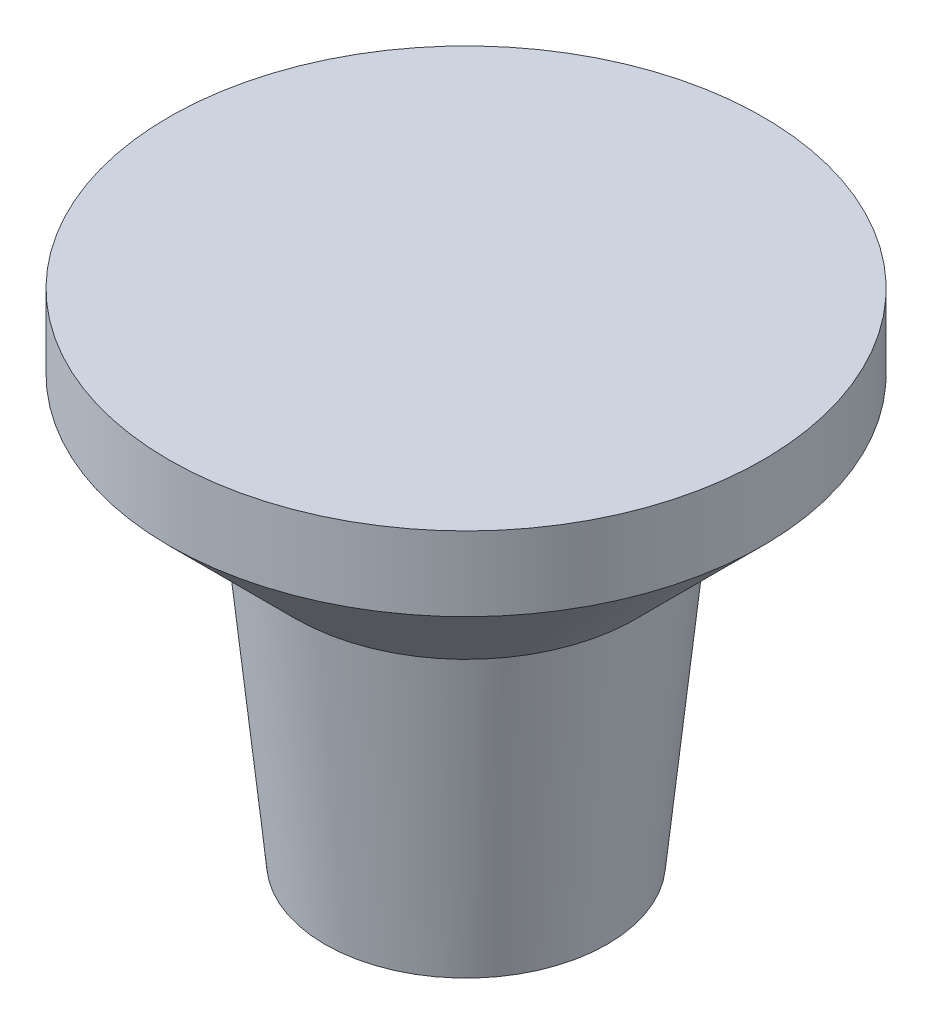
SolidWorks part; units mm, degrees
ref_plane "Płaszczyzna przednia" through (0, 0, 0) normal (0, 0, 1) x (1, 0, 0)
ref_plane "Płaszczyzna górna" through (0, 0, 0) normal (0, 1, 0) x (1, 0, 0)
ref_plane "Płaszczyzna prawa" through (0, 0, 0) normal (1, 0, 0) x (0, 0, -1)
ref_axis "Axis1" through (0, 55, 0) along (0, -1, 0)
sketch "Sketch1" plane through (0, 0, 0) normal (0, 0, 1) x (1, 0, 0)
  line L0 (0, 0) -> (3.8, 0)
  line L1 (3.8, 0) -> (4.6, 8)
  line L2 (4.6, 8) -> (8, 11.4)
  line L3 (8, 11.4) -> (8, 13.4)
  line L4 (8, 13.4) -> (0, 13.4)
  line L5 (0, 55) -> (0, -55) construction
  line L6 (0, 13.4) -> (0, 0)
  dimension "D1" = 45
  dimension "D2" = 2
  dimension "D3" = 3.8
  dimension "D4" = 4.6
  dimension "D5" = 8
  dimension "D6" = 8
revolve "Revolve1" add sketch "Sketch1" angle 360 about axis through (0, 55, 0) along (0, -1, 0)
